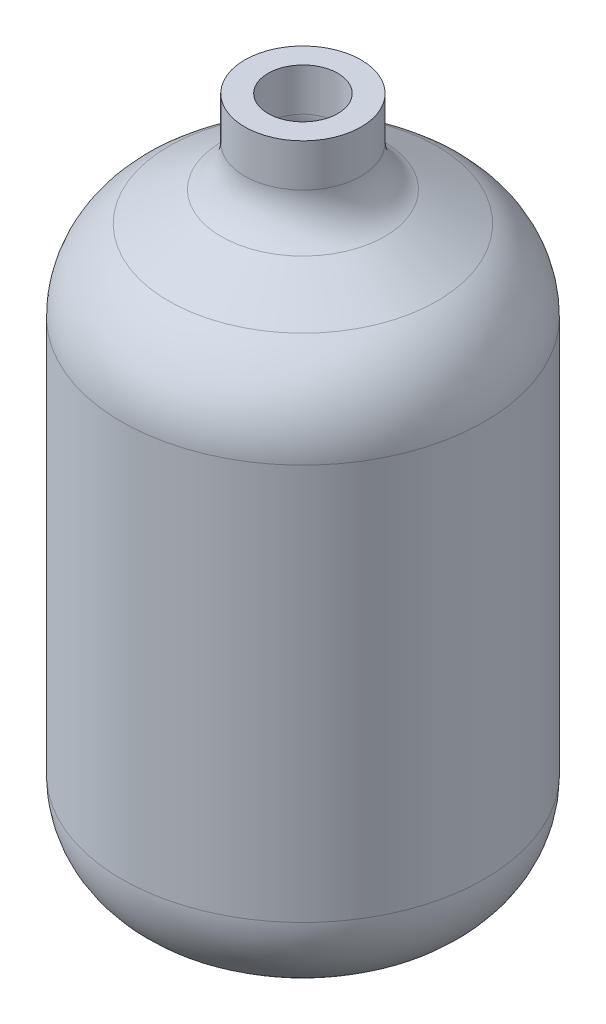
SolidWorks part; units mm, degrees
material "Zoltek Panex 33"
ref_plane "Front Plane" through (0, 0, 0) normal (0, 0, 1) x (1, 0, 0)
ref_plane "Top Plane" through (0, 0, 0) normal (0, 1, 0) x (1, 0, 0)
ref_plane "Right Plane" through (0, 0, 0) normal (1, 0, 0) x (0, 0, -1)
sketch "Sketch1" plane through (0, 0, 0) normal (0, 0, 1) x (1, 0, 0)
  line L0 (0, 0) -> (0, 50000) construction
  line L1 (-10.0341, -23.334) -> (-34.1641, -12.9576)
  line L2 (-49.53, 10.3764) -> (-49.53, 118.5406)
  line L3 (-36.642, 140.6451) -> (-22.319, 148.7525)
  line L4 (-15.875, 159.8047) -> (-15.875, 171.45)
  line L5 (-15.875, 171.45) -> (0, 171.45)
  line L8 (0, 171.45) -> (0, -25.4)
  arc A0 (-34.1641, -12.9576) -> (-49.53, 10.3764) centre (-24.13, 10.3764) cw
  arc A1 (-49.53, 118.5406) -> (-36.642, 140.6451) centre (-24.13, 118.5406) cw
  arc A2 (-22.319, 148.7525) -> (-15.875, 159.8047) centre (-28.575, 159.8047) ccw
  arc A3 (0, -25.4) -> (-10.0341, -23.334) centre (0, 0) cw
  point P10 (-49.53, -6.35)
  point P14 (-49.53, 133.35)
  point P17 (-15.875, 152.4)
  dimension "D7" = 25.4
  dimension "D8" = 12.7
  dimension "D9" = 25.4
  dimension "D1" = 99.06
  dimension "D2" = 19.05
  dimension "D3" = 19.05
  dimension "D4" = 19.05
  dimension "D5" = 31.75
  dimension "D6" = 196.85
revolve "Revolve1" add sketch "Sketch1" angle 360 about L0
shell "Shell1" thickness 6.35
